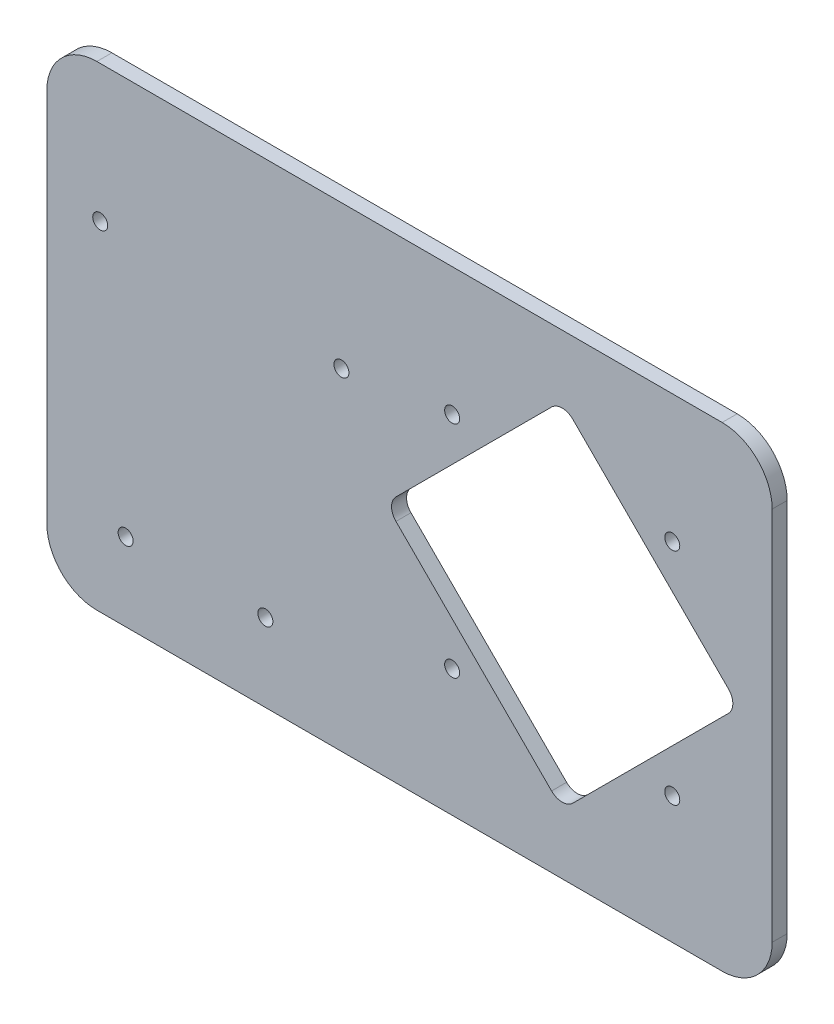
SolidWorks part; units mm, degrees
ref_plane "Plan de face" through (0, 0, 0) normal (0, 0, 1) x (1, 0, 0)
ref_plane "Plan de dessus" through (0, 0, 0) normal (0, 1, 0) x (1, 0, 0)
ref_plane "Plan de droite" through (0, 0, 0) normal (1, 0, 0) x (0, 0, -1)
sketch "Esquisse15" plane through (0, 0, 0) normal (0, 0, 1) x (1, 0, 0)
  line L0 (156.838, -41.0048) -> (200.8413, -85.0081) construction
  line L1 (210.8121, -15.3975) -> (85.8121, -15.3975)
  line L2 (220.8121, -25.3975) -> (220.8121, -100.3975)
  line L3 (210.8121, -110.3975) -> (85.8121, -110.3975)
  line L4 (75.8121, -25.3975) -> (75.8121, -100.3975)
  line L5 (200.8413, -41.0048) -> (156.838, -85.0081) construction
  line L6 (180.9609, -29.7724) -> (212.0736, -60.8851)
  line L7 (212.0736, -65.1278) -> (180.9609, -96.2405)
  line L8 (176.7183, -96.2405) -> (145.6056, -65.1278)
  line L9 (145.6056, -60.8851) -> (176.7183, -29.7724)
  arc A0 (220.8121, -100.3975) -> (210.8121, -110.3975) centre (210.8121, -100.3975) cw
  arc A1 (210.8121, -15.3975) -> (220.8121, -25.3975) centre (210.8121, -25.3975) cw
  arc A2 (85.8121, -15.3975) -> (75.8121, -25.3975) centre (85.8121, -25.3975) ccw
  arc A3 (85.8121, -110.3975) -> (75.8121, -100.3975) centre (85.8121, -100.3975) cw
  circle A4 centre (156.838, -85.0081) radius 1.5
  circle A5 centre (156.838, -41.0048) radius 1.5
  circle A6 centre (200.8413, -41.0048) radius 1.5
  circle A7 centre (200.8413, -85.0081) radius 1.5
  arc A8 (180.9609, -96.2405) -> (176.7183, -96.2405) centre (178.8396, -94.1191) cw
  arc A9 (212.0736, -60.8851) -> (212.0736, -65.1278) centre (209.9523, -63.0064) cw
  arc A10 (180.9609, -29.7724) -> (176.7183, -29.7724) centre (178.8396, -31.8937) ccw
  arc A11 (145.6056, -65.1278) -> (145.6056, -60.8851) centre (147.7269, -63.0064) cw
  circle A12 centre (86.4844, -42.7442) radius 1.5
  circle A13 centre (134.704, -44.1136) radius 1.5
  circle A14 centre (119.4999, -94.8142) radius 1.5
  circle A15 centre (91.5644, -94.8142) radius 1.5
  point P6 (220.8121, -110.3975)
  point P9 (220.8121, -15.3975)
  point P14 (75.8121, -110.3975)
  dimension "D3" = 10
  dimension "D9" = 3
  dimension "D10" = 3
  dimension "D11" = 3
  dimension "D12" = 3
  dimension "D17" = 3
  dimension "D18" = 3
  dimension "D19" = 3
  dimension "D20" = 3
  dimension "D21" = 3
  dimension "D22" = 52.07
  dimension "D23" = 5.08
  dimension "D1" = 145
  dimension "D2" = 95
  dimension "D4" = 62.23
  dimension "D5" = 62.23
  dimension "D6" = 31.115
  dimension "D7" = 31.115
  dimension "D8" = 45
  dimension "D13" = 25
  dimension "D14" = 25
  dimension "D15" = 25
  dimension "D16" = 25
extrude "Boss.-Extru.15" add sketch "Esquisse15" along normal blind 3 separate body
